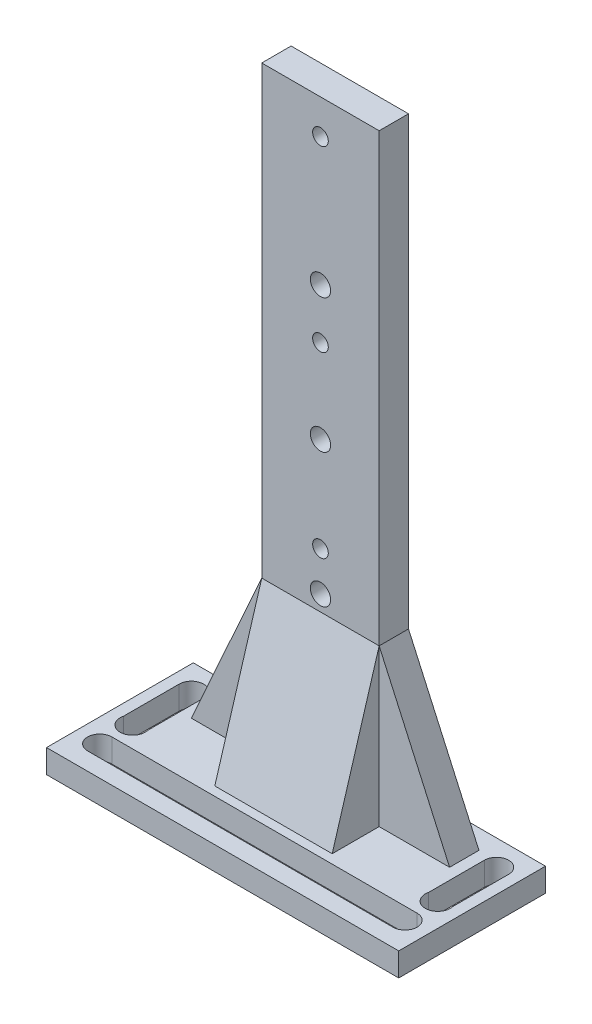
SolidWorks part; units mm, degrees
ref_plane "前视基准面" through (0, 0, 0) normal (0, 0, 1) x (1, 0, 0)
ref_plane "上视基准面" through (0, 0, 0) normal (0, 1, 0) x (1, 0, 0)
ref_plane "右视基准面" through (0, 0, 0) normal (1, 0, 0) x (0, 0, -1)
other "Configuration Table"
sketch "草图1" plane through (0, 0, 0) normal (0, 1, 0) x (1, 0, 0)
  line L1 (-45, 45) -> (45, 45)
  line L2 (-45, 45) -> (-45, -45)
  line L3 (-45, -45) -> (45, -45)
  line L4 (45, 45) -> (45, -45)
  line L5 (-45, 45) -> (45, -45) construction
  line L6 (-45, -45) -> (45, 45) construction
  point P0 (0, 0)
  dimension "D1" = 90
  dimension "D2" = 90
extrude "凸台-拉伸1" add sketch "草图1" along normal blind 6
sketch "草图2" plane through (0, 0, 0) normal (0, 1, 0) x (1, 0, 0)
  line L1 (-15, 20) -> (15, 20)
  line L2 (-15, 20) -> (-15, -20)
  line L3 (-15, -20) -> (15, -20)
  line L4 (15, 20) -> (15, -20)
  line L5 (-15, 20) -> (15, -20) construction
  line L6 (-15, -20) -> (15, 20) construction
  point P0 (0, 0)
  dimension "D1" = 30
  dimension "D2" = 40
extrude "凸台-拉伸2" add sketch "草图2" along normal blind 160
sketch "草图7" plane through (0, 0, 0) normal (0, 0, 1) x (1, 0, 0)
  line L0 (-15, 46) -> (-33, 6)
  line L1 (-15, 160) -> (-15, 6) construction
  line L2 (-45, 6) -> (45, 6) construction
  line L3 (-33, 6) -> (-15, 6)
  line L4 (-15, 6) -> (-15, 46)
  dimension "D1" = 18
  dimension "D2" = 40
extrude "凸台-拉伸3" add sketch "草图7" along normal up to surface (20 mm away) up to face at (0, 83, 20)
sketch "草图8" plane through (0, 0, 0) normal (0, 1, 0) x (1, 0, 0)
  line L0 (45, 45) -> (-45, 45) construction
  line L1 (-45, 45) -> (-45, -45) construction
  circle A0 centre (-39, 37.4) radius 3.1
  dimension "D2" = 6.2
  dimension "D1" = 7.6
  dimension "D3" = 6
extrude "切除-拉伸2" cut sketch "草图8" along normal up to surface (6 mm away) up to face at (-11, 6, 0)
sketch "草图15" plane through (0, 0, 0) normal (1, 0, 0) x (0, 0, -1)
  line L1 (-20, 46) -> (-20, 6)
  line L6 (-20, 46) -> (-32, 6)
  line L7 (-20, 160) -> (-20, 6) construction
  line L12 (-45, 6) -> (45, 6) construction
  line L13 (-32, 6) -> (-20, 6)
  dimension "D1" = 12
  dimension "D2" = 40
extrude "凸台-拉伸4" add sketch "草图15" along normal blind 15 and the other way blind 15
mirror "镜向11" about plane through (0, 0, 0) normal (0, 0, 1) of "凸台-拉伸4"
sketch "草图17" plane through (0, 0, 0) normal (1, 0, 0) x (0, 0, -1)
  line L0 (-20, 160) -> (-20, 46) construction
  line L1 (12.5, 160) -> (-12.5, 160)
  line L2 (12.5, 160) -> (12.5, 6)
  line L3 (12.5, 6) -> (-12.5, 6)
  line L4 (-12.5, 160) -> (-12.5, 6)
  line L5 (20, 160) -> (20, 46) construction
  line L6 (32, 6) -> (-32, 6) construction
  line L7 (-20, 160) -> (20, 160) construction
  line L8 (-45, 0) -> (45, 0) construction
  dimension "D1" = 25
  dimension "D2" = 7.5
  dimension "D3" = 7.5
  dimension "D4" = 0
  dimension "D5" = 0
  dimension "D6" = 154
  dimension "D7" = 6
extrude "切除-拉伸4" cut sketch "草图17" against normal through all and the other way through all
sketch "草图21" plane through (0, 0, 0) normal (1, 0, 0) x (0, 0, -1)
  line L0 (-7.5, 6) -> (7.5, 6)
  line L1 (32, 6) -> (-32, 6) construction
  line L2 (7.5, 6) -> (7.5, 0)
  line L3 (-45, 0) -> (45, 0) construction
  line L4 (7.5, 0) -> (-7.5, 0)
  line L5 (-7.5, 0) -> (-7.5, 6)
  line L6 (-20, 160) -> (-20, 46) construction
  line L7 (20, 160) -> (20, 46) construction
  line L8 (-12.5, 6) -> (-12.5, 160) construction
  dimension "D1" = 15
  dimension "D2" = 12.5
  dimension "D3" = 12.5
  dimension "D4" = 5
extrude "切除-拉伸8" cut sketch "草图21" against normal through all
mirror "镜向12" about plane through (0, 0, 0) normal (1, 0, 0) of "切除-拉伸2"
sketch "草图23" plane through (0, 0, 0) normal (0, 1, 0) x (1, 0, 0)
  line L0 (-39, 40.5) -> (39, 40.5)
  line L1 (39, 40.5) -> (39, 34.3)
  line L2 (39, 34.3) -> (-39, 34.3)
  line L3 (-39, 34.3) -> (-39, 40.5)
  circle A0 centre (-39, 37.4) radius 3.1 construction
  circle A1 centre (39, 37.4) radius 3.1 construction
extrude "切除-拉伸9" cut sketch "草图23" along normal through all
mirror "镜向13" about plane through (0, 0, 0) normal (0, 0, 1) of "切除-拉伸9"
mirror "镜向14" about plane through (0, 0, 0) normal (0, 0, 1) of "镜向12", "切除-拉伸2"
sketch "草图25" plane through (0, 0, 0) normal (0, 1, 0) x (1, 0, 0)
  line L0 (42.1, -14) -> (42.1, -29)
  line L1 (42.1, -29) -> (35.8707, -29)
  line L2 (35.8707, -29) -> (35.8707, -14)
  line L3 (35.8707, -14) -> (42.1, -14)
  line L4 (-45, -45) -> (45, -45) construction
  dimension "D1" = 15
  dimension "15" = 16
extrude "切除-拉伸10" cut sketch "草图25" along normal through all
sketch "草图26" plane through (0, 0, 0) normal (0, 1, 0) x (1, 0, 0)
  line L0 (35.8707, -14) -> (42.1, -14) construction
  circle A0 centre (38.9854, -14) radius 3.1146
extrude "切除-拉伸11" cut sketch "草图26" along normal through all
sketch "草图27" plane through (0, 0, 0) normal (0, 1, 0) x (1, 0, 0)
  line L0 (42.1, -29) -> (35.8707, -29) construction
  circle A0 centre (38.9854, -29) radius 3.2023
extrude "切除-拉伸12" cut sketch "草图27" along normal through all
mirror "镜向15" about plane through (0, 0, 0) normal (1, 0, 0) of "切除-拉伸10"
mirror "镜向16" about plane through (0, 0, 0) normal (1, 0, 0) of "切除-拉伸11"
mirror "镜向17" about plane through (0, 0, 0) normal (1, 0, 0) of "切除-拉伸12"
mirror "镜向23" about plane through (0, 0, 0) normal (1, 0, 0) of "凸台-拉伸3"
sketch "草图28" plane through (0, 0, 0) normal (0, 1, 0) x (1, 0, 0)
  line L0 (45, 0) -> (0, 0)
  line L1 (45, -45) -> (45, 45) construction
  line L2 (0, 0) -> (0, 7.5)
  line L3 (0, 7.5) -> (-45, 7.5)
  line L4 (-45, 7.5) -> (-45, 45)
  line L5 (-45, 45) -> (45, 45)
  line L6 (45, 45) -> (45, 0)
extrude "切除-拉伸13" cut sketch "草图28" along normal through all
sketch "草图29" plane through (0, 0, 0) normal (0, 1, 0) x (1, 0, 0)
  line L0 (0, -7.5) -> (45, -7.5)
  line L1 (45, -45) -> (45, 0) construction
  line L2 (45, -7.5) -> (45, 0)
  line L3 (45, 0) -> (0, 0)
  line L4 (0, 0) -> (0, -7.5)
extrude "切除-拉伸14" cut sketch "草图29" along normal through all
sketch "草图30" plane through (0, 0, 0) normal (1, 0, 0) x (0, 0, -1)
  line L0 (-12.5, 46) -> (-7.5, 46)
  line L1 (-7.5, 46) -> (-7.5, 6)
  line L2 (-12.5, 46) -> (-12.5, 6)
  line L3 (-20, 6) -> (-7.5, 6) construction
  line L4 (-12.5, 6) -> (-7.5, 6)
extrude "切除-拉伸15" cut sketch "草图30" along normal through all
sketch "草图31" plane through (0, 0, 0) normal (0, 0, 1) x (1, 0, 0)
  line L0 (-45, 0) -> (45, 0) construction
  circle A0 centre (0, 60) radius 2
  dimension "D1" = 4
  dimension "D2" = 60
extrude "切除-拉伸16" cut sketch "草图31" along normal through all
pattern_linear "阵列(线性)2" count 3 spacing 45.6 along (0, 1, 0) of "切除-拉伸16"
sketch "草图32" plane through (0, 0, 0) normal (0, 0, 1) x (1, 0, 0)
  line L0 (-45, 0) -> (45, 0) construction
  circle A0 centre (0, 50) radius 2.6
  dimension "D1" = 5.2
  dimension "D2" = 50
extrude "切除-拉伸17" cut sketch "草图32" along normal through all
pattern_linear "阵列(线性)3" count 3 spacing 34.2 along (0, 1, 0) of "切除-拉伸17"
